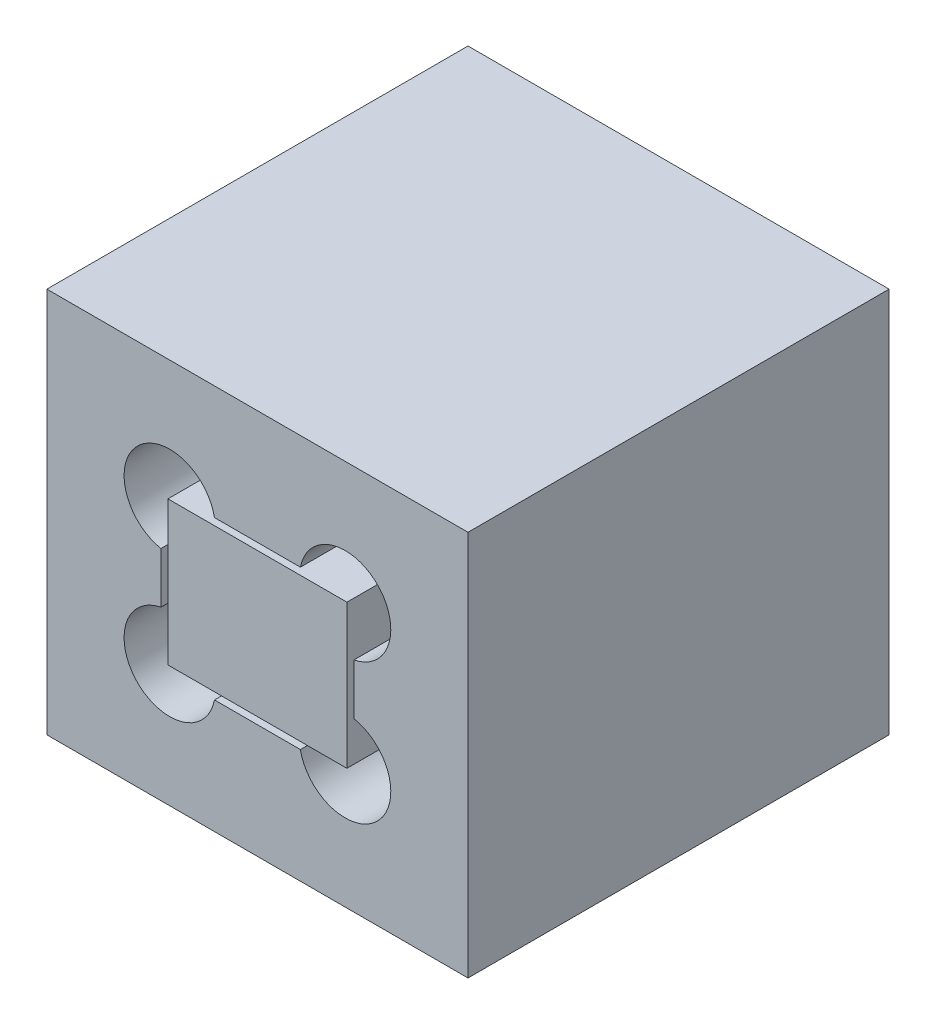
SolidWorks part; units mm, degrees
material "ABS"
ref_plane "Plan de face" through (0, 0, 0) normal (0, 0, 1) x (1, 0, 0)
ref_plane "Plan de dessus" through (0, 0, 0) normal (0, 1, 0) x (1, 0, 0)
ref_plane "Plan de droite" through (0, 0, 0) normal (1, 0, 0) x (0, 0, -1)
sketch "Esquisse1" plane through (0, 0, 0) normal (0, 0, 1) x (1, 0, 0)
  line L1 (0, 0) -> (12, 0)
  line L2 (0, 0) -> (0, 11)
  line L3 (0, 11) -> (12, 11)
  line L4 (12, 0) -> (12, 11)
  dimension "D1" = 12
  dimension "D2" = 11
extrude "Extrusion1" add sketch "Esquisse1" along normal blind 12
sketch "Esquisse2" plane through (0, 0, 12) normal (0, 0, 1) x (1, 0, 0)
  line L0 (0, 5.5) -> (12, 5.5) construction
  line L1 (0, 11) -> (0, 0) construction
  line L2 (12, 0) -> (12, 11) construction
  line L3 (6, 11) -> (6, 0) construction
  line L4 (12, 11) -> (0, 11) construction
  line L5 (0, 0) -> (12, 0) construction
  line L6 (4.7757, 7.75) -> (7.2243, 7.75)
  line L7 (8.75, 6.2243) -> (8.75, 4.7757)
  line L8 (7.2243, 3.25) -> (4.7757, 3.25)
  line L9 (3.25, 4.7757) -> (3.25, 6.2243)
  arc A3 (3.25, 4.7757) -> (4.7757, 3.25) centre (3.5, 3.5) ccw
  arc A4 (3.25, 6.2243) -> (4.7757, 7.75) centre (3.5, 7.5) cw
  arc A6 (8.75, 4.7757) -> (7.2243, 3.25) centre (8.5, 3.5) cw
  arc A7 (8.75, 6.2243) -> (7.2243, 7.75) centre (8.5, 7.5) ccw
  dimension "D1" = 2
  dimension "D2" = 2.5
extrude "Enlèv. mat.-Extru.1" cut sketch "Esquisse2" against normal blind 2.5
sketch "Esquisse3" plane through (0, 0, 9.5) normal (0, 0, 1) x (1, 0, 0)
  line L26 (8.55, 3.45) -> (8.55, 7.55)
  line L27 (3.45, 3.45) -> (8.55, 3.45)
  line L28 (3.45, 7.55) -> (3.45, 3.45)
  line L29 (8.55, 7.55) -> (3.45, 7.55)
extrude "Extrusion2" add sketch "Esquisse3" along normal up to surface (2.5 mm away) up to face at (6, 5.5, 12)
